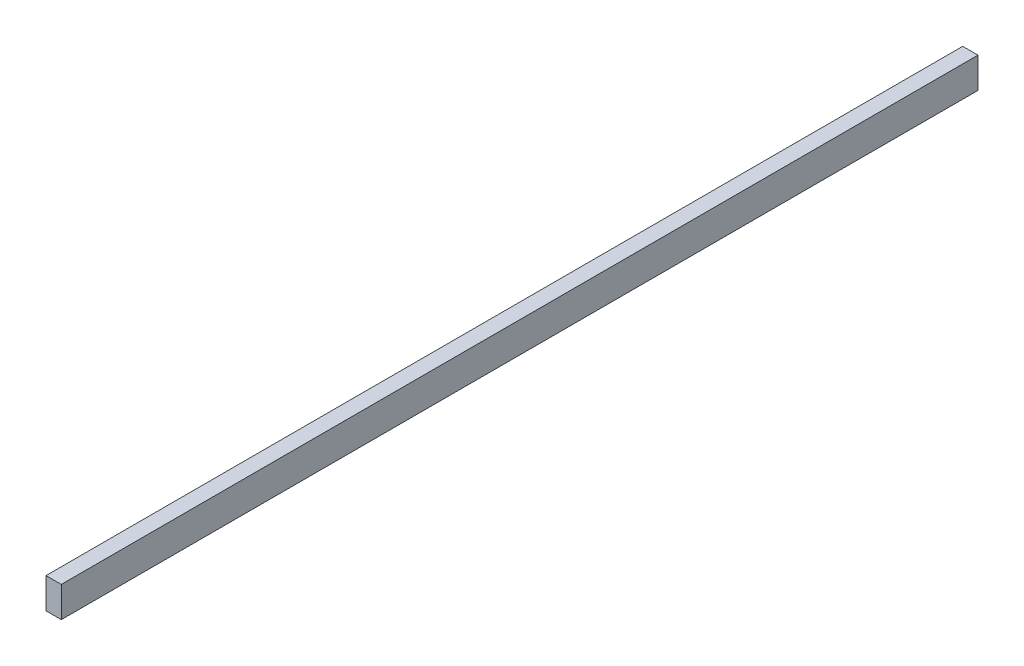
SolidWorks part; units mm, degrees
ref_plane "Front Plane" through (0, 0, 0) normal (0, 0, 1) x (1, 0, 0)
ref_plane "Top Plane" through (0, 0, 0) normal (0, 1, 0) x (1, 0, 0)
ref_plane "Right Plane" through (0, 0, 0) normal (1, 0, 0) x (0, 0, -1)
sketch "Sketch1" plane through (0, 0, 0) normal (0, 0, 1) x (1, 0, 0)
  line L1 (-78.7671, 27.3595) -> (-53.3671, 27.3595)
  line L2 (-78.7671, 27.3595) -> (-78.7671, -23.4405)
  line L3 (-78.7671, -23.4405) -> (-53.3671, -23.4405)
  line L4 (-53.3671, 27.3595) -> (-53.3671, -23.4405)
  dimension "D1" = 50.8
  dimension "D2" = 25.4
extrude "Boss-Extrude1" add sketch "Sketch1" along normal blind 1524
